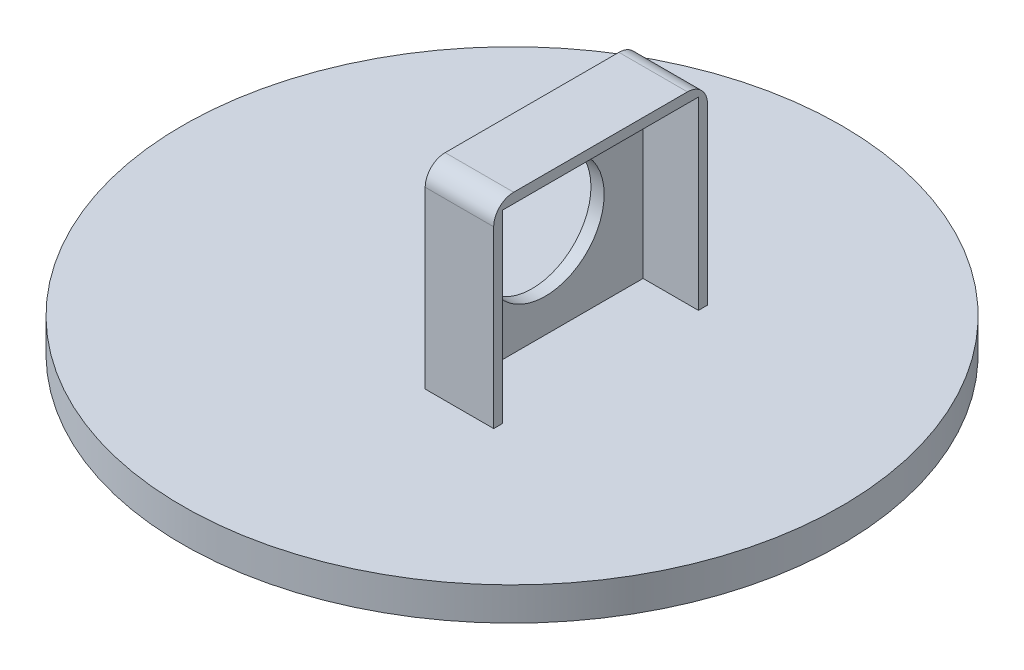
SolidWorks part; units mm, degrees
ref_plane "前视基准面" through (0, 0, 0) normal (0, 0, 1) x (1, 0, 0)
ref_plane "上视基准面" through (0, 0, 0) normal (0, 1, 0) x (1, 0, 0)
ref_plane "右视基准面" through (0, 0, 0) normal (1, 0, 0) x (0, 0, -1)
other "Configuration Table"
sketch "草图1" plane through (0, 0, 0) normal (0, 1, 0) x (1, 0, 0)
  circle A0 centre (0, 0) radius 165
extrude "凸台-拉伸1" add sketch "草图1" along normal blind 16.6
sketch "草图2" plane through (0, 0, 0) normal (0, -1, 0) x (1, 0, 0)
  line L0 (0, 165) -> (0, -165) construction
  line L1 (-165, 0) -> (165, 0) construction
  circle A0 centre (0, 0) radius 165 construction
  circle A1 centre (0, 0) radius 30
extrude "切除-拉伸1" cut sketch "草图2" against normal blind 6.6
sketch "草图3" plane through (0, 6.6, 0) normal (0, -1, 0) x (1, 0, 0)
  line L0 (0, 30) -> (0, -30) construction
  line L1 (-30, 0) -> (30, 0) construction
  circle A0 centre (0, 0) radius 30 construction
  circle A1 centre (0, 0) radius 30 construction
  circle A2 centre (0, 0) radius 2.5
  circle A3 centre (0, 17.25) radius 2
  circle A4 centre (0, -17.25) radius 2
  dimension "D1" = 34.5
extrude "切除-拉伸2" cut sketch "草图3" against normal through all
ref_plane "基准面1" through (10, 0, 0) normal (1, 0, 0) x (0, 0, -1)
sketch "草图4" plane through (10, 0, 0) normal (1, 0, 0) x (0, 0, -1)
  line L0 (165, 16.6) -> (-165, 16.6) construction
  line L1 (-53.5, 16.6) -> (53.5, 16.6)
  line L2 (-53.5, 16.6) -> (-53.5, 114.1)
  line L3 (-53.5, 114.1) -> (53.5, 114.1)
  line L4 (53.5, 16.6) -> (53.5, 114.1)
  line L5 (0, 0) -> (0, 161.3354) construction
  dimension "D1" = 107
  dimension "D2" = 97.5
extrude "凸台-拉伸2" add sketch "草图4" along normal blind 34.3
sketch "草图5" plane through (44.3, 0, 0) normal (1, 0, 0) x (0, 0, -1)
  line L0 (-53.5, 16.6) -> (53.5, 16.6) construction
  line L1 (-49, 16.6) -> (49, 16.6)
  line L2 (-49, 16.6) -> (-49, 109.1)
  line L3 (-49, 109.1) -> (49, 109.1)
  line L4 (49, 16.6) -> (49, 109.1)
  line L5 (0, 0) -> (0, 152.146) construction
  dimension "D1" = 98
  dimension "D2" = 92.5
extrude "切除-拉伸3" cut sketch "草图5" against normal blind 27.7
sketch "草图6" plane through (16.6, 0, 0) normal (1, 0, 0) x (0, 0, -1)
  circle A0 centre (0, 62.85) radius 29.5
extrude "切除-拉伸4" cut sketch "草图6" against normal blind 6.6
fillet "圆角1" radius 10 2 edges at (27.15, 114.1, 53.5) (27.15, 114.1, -53.5)
